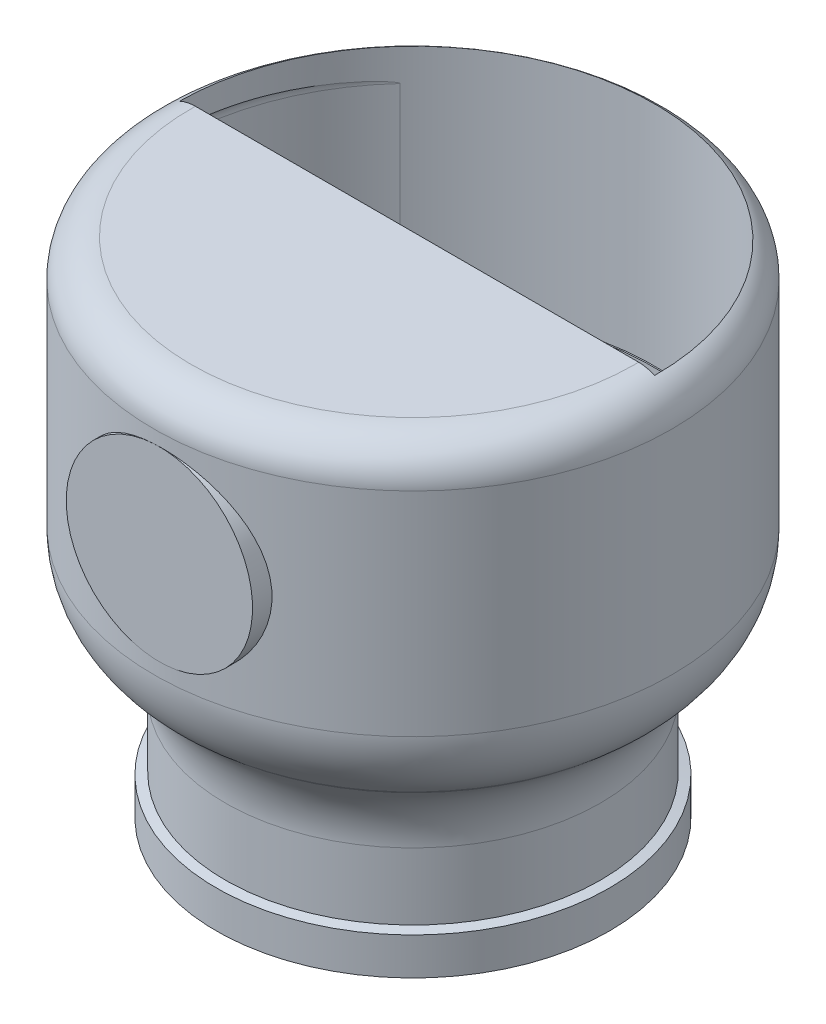
SolidWorks part; units mm, degrees
ref_plane "Front Plane" through (0, 0, 0) normal (0, 0, 1) x (1, 0, 0)
ref_plane "Top Plane" through (0, 0, 0) normal (0, 1, 0) x (1, 0, 0)
ref_plane "Right Plane" through (0, 0, 0) normal (1, 0, 0) x (0, 0, -1)
sketch "Sketch1" plane through (0, 0, 0) normal (0, 0, 1) x (1, 0, 0)
  line L0 (2.7649, 7.8218) -> (2.7649, 58.3592) construction
  line L1 (20.9, 0) -> (23.8716, 0)
  line L2 (23.8716, 0) -> (23.8716, 4)
  line L3 (23.8716, 4) -> (22.9, 4.2367)
  line L4 (22.9, 4.2367) -> (22.9, 11.4043)
  line L6 (20.9, 0) -> (20.9, 14)
  line L8 (2.7649, 52) -> (2.7649, 54)
  line L10 (17.2603, 17) -> (2.7649, 17)
  line L12 (19.9, 15) -> (2.7649, 15)
  line L13 (2.7649, 17) -> (2.7649, 15)
  line L15 (23.6882, 19.3396) -> (24.9883, 20.4305)
  line L16 (28.5604, 28.091) -> (28.5604, 50)
  line L17 (26.4721, 19.0648) -> (26.9883, 19.4979)
  line L18 (30.5604, 27.1583) -> (30.5604, 50)
  line L19 (26.5604, 52) -> (2.7649, 52)
  line L20 (26.5604, 54) -> (2.7649, 54)
  arc A0 (28.5604, 50) -> (26.5604, 52) centre (26.5604, 50) ccw
  arc A1 (30.5604, 50) -> (26.5604, 54) centre (26.5604, 50) ccw
  arc A2 (26.4721, 19.0648) -> (22.9, 11.4043) centre (32.9, 11.4043) ccw
  arc A3 (26.9883, 19.4979) -> (30.5604, 27.1583) centre (20.5604, 27.1583) ccw
  arc A4 (24.9883, 20.4305) -> (28.5604, 28.091) centre (18.5604, 28.091) ccw
  arc A5 (17.2603, 17) -> (23.6882, 19.3396) centre (17.2603, 27) ccw
  arc A6 (20.9, 14) -> (19.9, 15) centre (19.9, 14) ccw
  point P11 (22.9, 54)
  point P28 (28.5604, 23.4279)
  point P31 (20.9, 17)
  dimension "D8" = 2
  dimension "D9" = 4
  dimension "D4" = 2
  dimension "D16" = 10
  dimension "D17" = 10
  dimension "D18" = 10
  dimension "D19" = 1
  dimension "D1" = 2
  dimension "D2" = 4
  dimension "D3" = 1
  dimension "D5" = 140
  dimension "D6" = 2
  dimension "D7" = 2.9716
  dimension "D10" = 2
  dimension "D11" = 15
  dimension "D12" = 35
  dimension "D13" = 37
  dimension "D14" = 2
  dimension "D15" = 10
revolve "Revolve1" add sketch "Sketch1" angle 360 about L0
ref_plane "Plane1" through (0, 4, 0) normal (0, 1, 0) x (1, 0, 0)
sketch "Sketch3" plane through (0, 0, 0) normal (0, 0, 1) x (1, 0, 0)
  point P0 (1.2404, 19.1989)
ref_point "Point1"
ref_plane "Plane2" through (0, 0, 22.9) normal (0, 0, 1) x (1, 0, 0)
ref_plane "Plane3" through (0, 0, 27.7955) normal (0, 0, 1) x (1, 0, 0)
ref_plane "Plane4" through (0, 54, 0) normal (0, 1, 0) x (1, 0, 0)
sketch "Sketch9" plane through (0, 54, 0) normal (0, 1, 0) x (1, 0, 0)
  line L0 (-22.7351, 0.4376) -> (28.2649, 0.4376)
  arc A0 (28.2649, 0.4376) -> (-22.7351, 0.4376) centre (2.7649, 0.4376) ccw
  circle A3 centre (2.7649, 0) radius 23.7955 construction
  point P1 (0, 0)
  dimension "D1" = 51
  dimension "D3" = 25.5
  dimension "D2" = 25.5
extrude "Cut-Extrude2" cut sketch "Sketch9" against normal blind 25
sketch "Sketch10" plane through (0, 0, 27.7955) normal (0, 0, 1) x (1, 0, 0)
  line L0 (30.5604, 27.1583) -> (-25.0306, 27.1583) construction
  circle A0 centre (3.3463, 38.6583) radius 10
  dimension "D1" = 20
  dimension "D2" = 11.5
extrude "Boss-Extrude1" add sketch "Sketch10" against normal blind 5
ref_plane "Plane5" through (0, 17, 0) normal (0, 1, 0) x (1, 0, 0)
sketch "Sketch11" plane through (0, 17, 0) normal (0, 1, 0) x (1, 0, 0)
  line L0 (-11.7305, 0) -> (17.2603, 0)
  circle A0 centre (2.7649, 0) radius 14.4954 construction
  arc A1 (-11.7305, 0) -> (17.2603, 0) centre (2.7649, 0) cw
extrude "Cut-Extrude3" cut sketch "Sketch11" against normal blind 10
